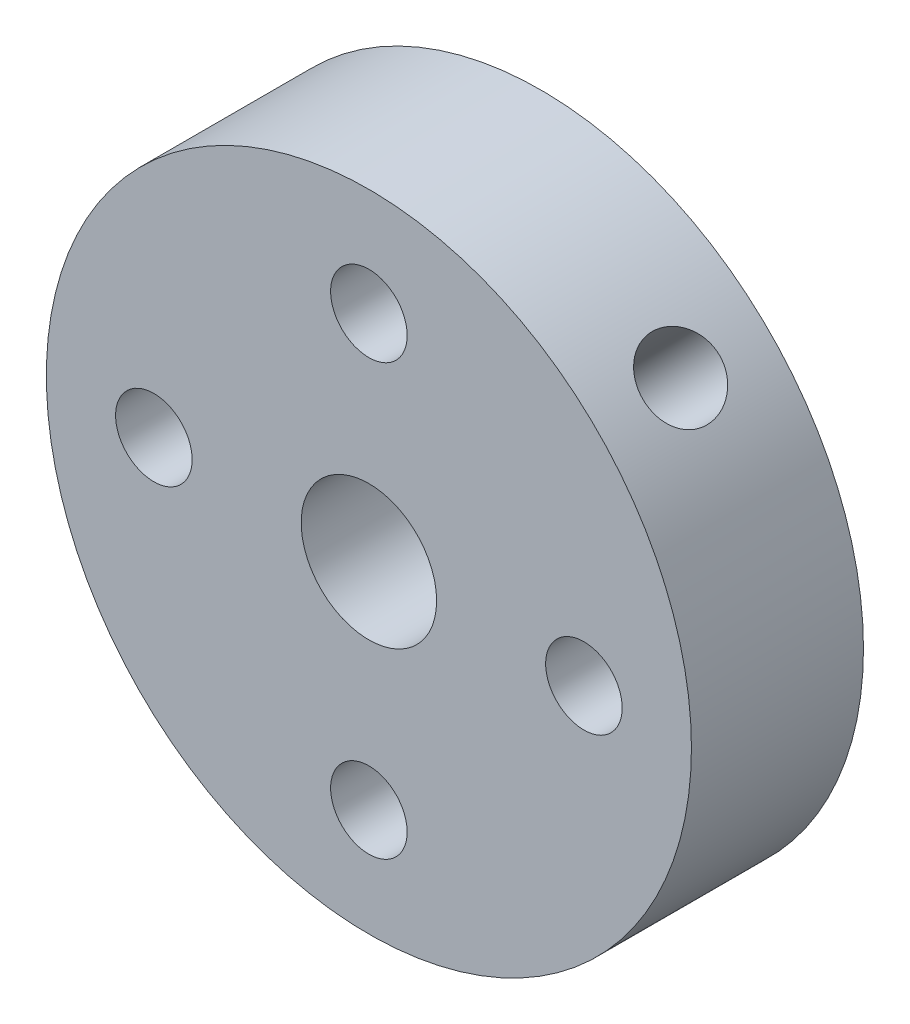
SolidWorks part; units mm, degrees
material "6061 Alloy"
ref_plane "Front Plane" through (0, 0, 0) normal (0, 0, 1) x (1, 0, 0)
ref_plane "Top Plane" through (0, 0, 0) normal (0, 1, 0) x (1, 0, 0)
ref_plane "Right Plane" through (0, 0, 0) normal (1, 0, 0) x (0, 0, -1)
sketch "Sketch1" plane through (0, 0, 0) normal (0, 0, 1) x (1, 0, 0)
  circle A0 centre (0, 0) radius 9.525
  circle A1 centre (0, 0) radius 2
  dimension "D1" = 19.05
  dimension "D2" = 4
extrude "Boss-Extrude1" add sketch "Sketch1" along normal blind 5.08
hole_wizard "#4-40 Tapped Hole3" positions "Sketch3" profile "Sketch2" tap size "#4-40" standard "Ansi Inch"
sketch "Sketch3" plane through (0, 0, 5.08) normal (0, 0, 1) x (1, 0, 0)
  point P0 (-6.35, 0)
  point P1 (6.35, 0)
  point P3 (0, 6.35)
  point P5 (0, -6.35)
  dimension "D1" = 6.35
  dimension "D2" = 6.35
  dimension "D3" = 6.35
  dimension "D4" = 6.35
cosmetic thread "Hole Thread1" parameters "D1"=5.08, "D2"=2.8448
cosmetic thread "Hole Thread2" parameters "D1"=5.08, "D2"=2.8448
cosmetic thread "Hole Thread3" parameters "D1"=5.08, "D2"=2.8448
cosmetic thread "Hole Thread4" parameters "D1"=5.08, "D2"=2.8448
sketch "Sketch2" plane through (-6.35, 0, 5.08) normal (1, 0, 0) x (0, -1, 0)
  line L0 (0, 0) -> (0, 8.2792)
  line L1 (0, 8.2792) -> (1.1303, 7.6)
  line L2 (1.1303, 7.6) -> (1.1303, 0)
  line L5 (1.1303, 0) -> (0, 0)
  line L10 (0, 8.2792) -> (-1.1303, 7.6) construction
  line L11 (0, -6.35) -> (0, 107.95) construction
  dimension "Tap Drill Dia." = 2.2606
  dimension "Tap Drill Depth" = 7.6
  dimension "Drill Angle" = 118
ref_plane "Plane1" through (0, 0, 2.54) normal (0, 0, 1) x (1, 0, 0)
sketch "Sketch10" plane through (0, 0, 2.54) normal (0, 0, 1) x (1, 0, 0)
  line L0 (-701.4729, -712.6523) -> (34372.1722, 34919.9618) construction
  circle A2 centre (6.35, 0) radius 1.1303 construction
  dimension "D1" = 4.5255
hole_wizard "#4-40 Tapped Hole2" positions "3DSketch5" profile "Sketch11" tap size "#4-40" standard "Ansi Inch"
sketch3d "3DSketch5"
  line L0 (-701.4729, -712.6523, 2.54) -> (34372.1722, 34919.9618, 2.54) construction
  point P0 (6.6817, 6.7882, 2.54)
sketch "Sketch11" plane through (6.6817, 6.7882, 2.54) normal (0, 0, 1) x (-0.7127, 0.7015, 0)
  line L0 (0, 0) -> (0, 8.2792)
  line L1 (0, 8.2792) -> (1.1303, 7.6)
  line L2 (1.1303, 7.6) -> (1.1303, 0)
  line L5 (1.1303, 0) -> (0, 0)
  line L10 (0, 8.2792) -> (-1.1303, 7.6) construction
  line L11 (0, -6.35) -> (0, 107.95) construction
  dimension "Tap Drill Dia." = 2.2606
  dimension "Tap Drill Depth" = 7.6
  dimension "Drill Angle" = 118
cosmetic thread "Hole Thread5" parameters "D1"=5.69, "D2"=2.8448
